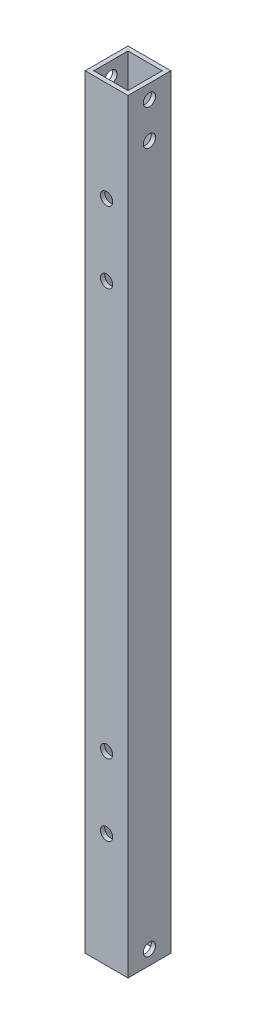
SolidWorks part; units mm, degrees
material "5052-H34"
ref_plane "正面" through (0, 0, 0) normal (0, 0, 1) x (1, 0, 0)
ref_plane "平面" through (0, 0, 0) normal (0, 1, 0) x (1, 0, 0)
ref_plane "右側面" through (0, 0, 0) normal (1, 0, 0) x (0, 0, -1)
sketch "ｽｹｯﾁ1" plane through (0, 0, 0) normal (0, 1, 0) x (1, 0, 0)
  line L1 (-7.5, 7.5) -> (7.5, 7.5)
  line L2 (-7.5, 7.5) -> (-7.5, -7.5)
  line L3 (-7.5, -7.5) -> (7.5, -7.5)
  line L4 (7.5, 7.5) -> (7.5, -7.5)
  line L5 (-7.5, 7.5) -> (7.5, -7.5) construction
  line L6 (-7.5, -7.5) -> (7.5, 7.5) construction
  point P0 (0, 0)
  dimension "D1" = 15
  dimension "D2" = 15
extrude "押し出し-薄板1" add sketch "ｽｹｯﾁ1" along normal blind 267.5 thin
sketch "ｽｹｯﾁ2" plane through (7.5, 0, 0) normal (-1, 0, 0) x (0, 0, 1)
  line L0 (0, 267.5) -> (0, 5) construction
  line L2 (-7.5, 267.5) -> (7.5, 267.5) construction
  circle A0 centre (0, 5) radius 2.15
  circle A1 centre (0, 262.5) radius 2.15
  circle A2 centre (0, 250) radius 2.15
  dimension "D2" = 4.3
  dimension "D1" = 262.5
  dimension "D3" = 5
  dimension "D4" = 12.5
extrude "ｶｯﾄ - 押し出し1" cut sketch "ｽｹｯﾁ2" along normal through all
sketch "ｽｹｯﾁ3" plane through (0, 0, 7.5) normal (0, 0, 1) x (1, 0, 0)
  line L0 (0, 267.5) -> (0, 207.5) construction
  line L1 (-7.5, 267.5) -> (7.5, 267.5) construction
  line L2 (0, 0) -> (0, 65) construction
  circle A0 centre (0, 207.5) radius 2.15
  circle A1 centre (0, 232.5) radius 2.15
  circle A2 centre (0, 65) radius 2.15
  circle A3 centre (0, 40) radius 2.15
  dimension "D1" = 4.3
  dimension "D3" = 35
  dimension "D2" = 25
  dimension "D4" = 25
  dimension "D5" = 40
extrude "ｶｯﾄ - 押し出し2" cut sketch "ｽｹｯﾁ3" against normal through all
